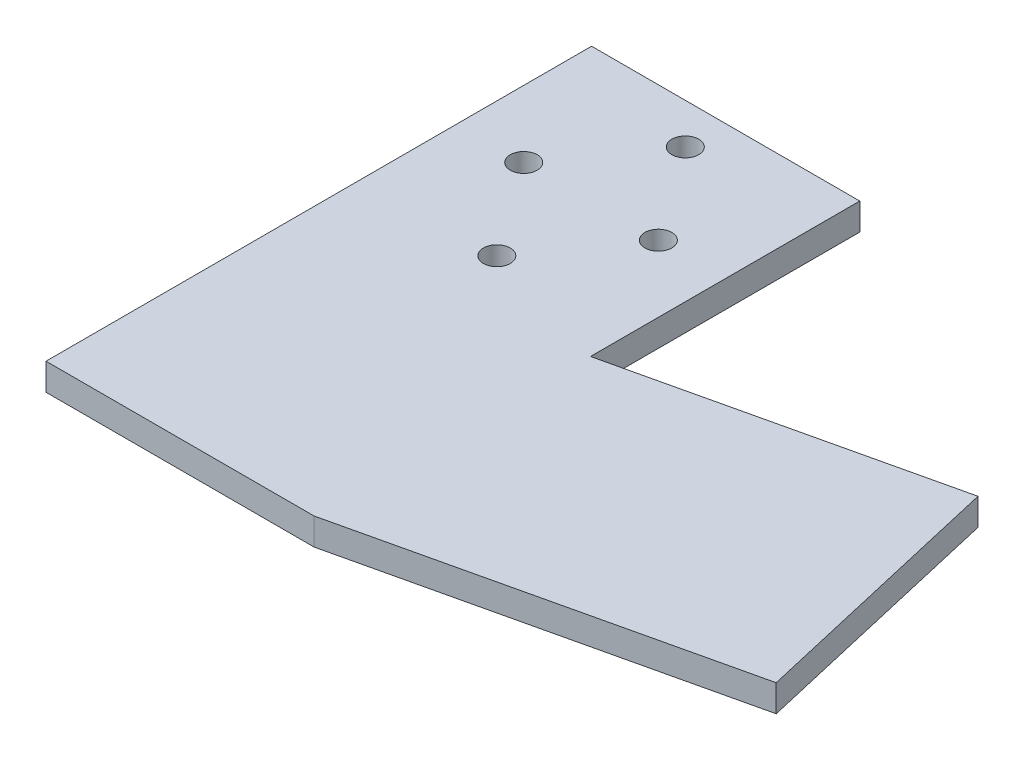
SolidWorks part; units mm, degrees
ref_plane "Front Plane" through (0, 0, 0) normal (0, 0, 1) x (1, 0, 0)
ref_plane "Top Plane" through (0, 0, 0) normal (0, 1, 0) x (1, 0, 0)
ref_plane "Right Plane" through (0, 0, 0) normal (1, 0, 0) x (0, 0, -1)
sketch "Sketch1" plane through (0, 0, 0) normal (0, 1, 0) x (1, 0, 0)
  line L0 (0, 0) -> (58.4622, 13.4971)
  line L2 (-49.8, 0) -> (-49.8, 50)
  line L3 (-49.8, 50) -> (0, 50)
  line L4 (0, 0) -> (0, 50)
  line L7 (58.4622, 13.4971) -> (69.7098, -35.2214)
  line L8 (69.7098, -35.2214) -> (0, -51.3152)
  line L9 (-49.8, 0) -> (-49.8, -51.3152)
  line L10 (-49.8, -51.3152) -> (0, -51.3152)
  point P0 (0, 0)
  point P6 (0, 0)
  point P10 (24.9, -65.0896)
  point P12 (0, 0)
  point P13 (0, 0)
  point P14 (0, 0)
  point P15 (0, 0)
  dimension "D1" = 49.8
  dimension "D2" = 50
  dimension "D3" = 77
  dimension "D4" = 50
  dimension "D5" = 49.8
  dimension "D6" = 60
extrude "Boss-Extrude1" add sketch "Sketch1" along normal blind 5
sketch "Sketch2" plane through (0, 5, 0) normal (0, 1, 0) x (1, 0, 0)
  line L0 (-24.9, 50) -> (-24.9, 0) construction
  line L1 (0, 50) -> (-49.8, 50) construction
  line L2 (-24.9, 25) -> (0, 25) construction
  line L3 (0, 0) -> (0, 50) construction
  line L4 (-24.9, 25) -> (-49.8, 25) construction
  line L5 (-49.8, 50) -> (-49.8, -51.3152) construction
  circle A0 centre (-24.9, 42.5) radius 2.5
  circle A1 centre (-24.9, 7.5) radius 2.5
  circle A2 centre (-12.4, 25) radius 2.5
  circle A3 centre (-37.4, 25) radius 2.5
  dimension "D2" = 5
  dimension "D1" = 17.5
  dimension "D3" = 12.5
extrude "Cut-Extrude1" cut sketch "Sketch2" against normal through all both and the other way through all
